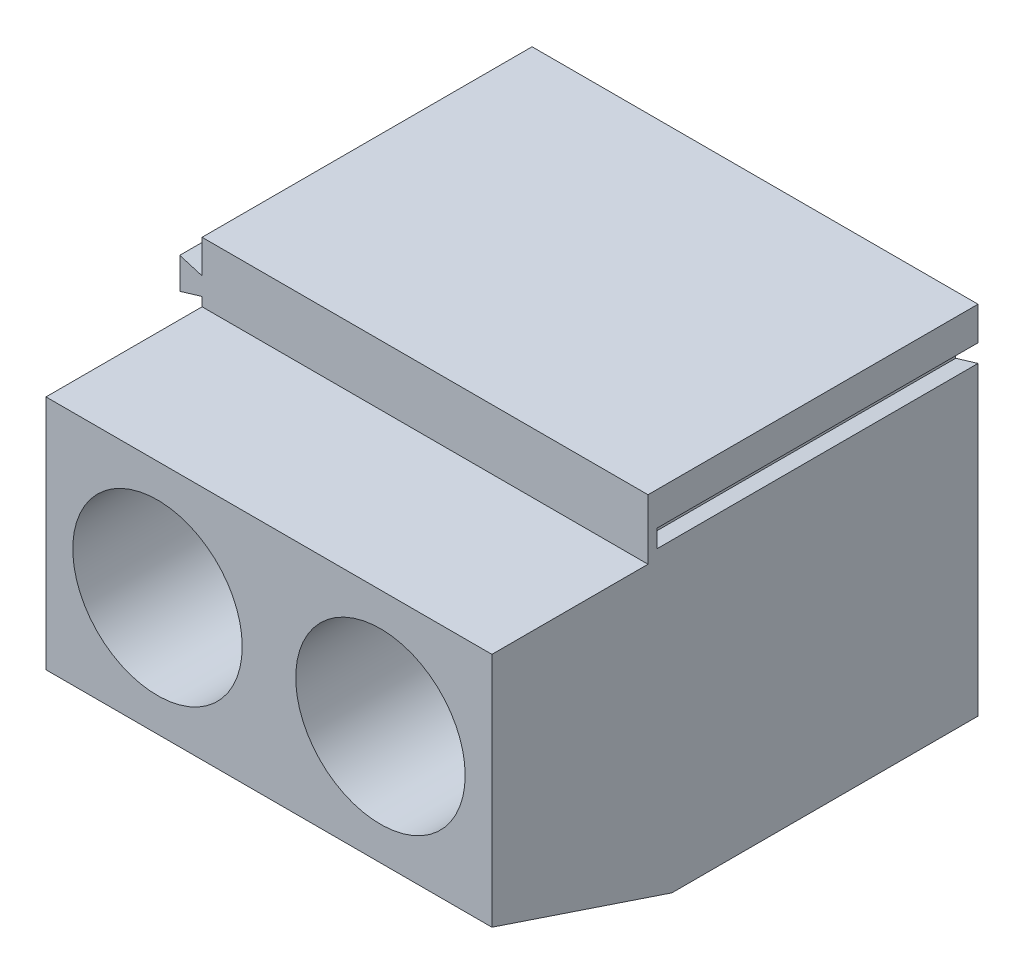
SolidWorks part; units mm, degrees
ref_plane "Front Plane" through (0, 0, 0) normal (0, 0, 1) x (1, 0, 0)
ref_plane "Top Plane" through (0, 0, 0) normal (0, 1, 0) x (1, 0, 0)
ref_plane "Right Plane" through (0, 0, 0) normal (1, 0, 0) x (0, 0, -1)
sketch "Sketch1" plane through (0, 0, 0) normal (0, 0, 1) x (1, 0, 0)
  line L1 (-5, 4) -> (5, 4)
  line L2 (-5, 4) -> (-5, -4)
  line L3 (-5, -4) -> (5, -4)
  line L4 (5, 4) -> (5, -4)
  line L5 (-5, 4) -> (5, -4) construction
  line L6 (-5, -4) -> (5, 4) construction
  point P0 (0, 0)
  dimension "D1" = 10
  dimension "D2" = 8
  dimension "D3" = 4
extrude "Boss-Extrude1" add sketch "Sketch1" along normal blind 10.9
chamfer "Chamfer1" distance 1.35 angle 71.5 1 edges at (0, -4, 10.9)
sketch "Sketch2" plane through (0, 4, 0) normal (0, 1, 0) x (1, 0, 0)
  line L0 (5, -10.9) -> (5, 0) construction
  line L1 (-5, -10.9) -> (5, -10.9)
  line L2 (-5, -10.9) -> (-5, -7.4)
  line L3 (-5, -7.4) -> (5, -7.4)
  line L4 (5, -10.9) -> (5, -7.4)
  dimension "D1" = 3.5
extrude "Cut-Extrude1" cut sketch "Sketch2" against normal blind 1.35
sketch "Sketch3" plane through (0, -4, 0) normal (0, -1, 0) x (1, 0, 0)
  line L0 (0, 0) -> (0, 6.8653) construction
  line L1 (-4.475, 5.65) -> (-0.475, 5.65)
  line L2 (-4.475, 5.65) -> (-4.475, 0.65)
  line L3 (-4.475, 0.65) -> (-0.475, 0.65)
  line L4 (-0.475, 5.65) -> (-0.475, 0.65)
  line L5 (0.475, 5.65) -> (4.475, 5.65)
  line L6 (0.475, 5.65) -> (0.475, 0.65)
  line L7 (0.475, 0.65) -> (4.475, 0.65)
  line L8 (4.475, 5.65) -> (4.475, 0.65)
  line L9 (-5, 0) -> (5, 0) construction
  line L10 (5, 6.8653) -> (-5, 6.8653) construction
  point P8 (4.3875, 1.8004)
  point P15 (0.4239, 5.65)
  dimension "D1" = 4
  dimension "D2" = 0.65
  dimension "D3" = 5
  dimension "D4" = 0.95
extrude "Cut-Extrude2" cut sketch "Sketch3" against normal blind 7
chamfer "Chamfer2" distance 1.2 angle 45 2 edges at (2.475, -4, 5.65) (-2.475, -4, 5.65)
sketch "Sketch4" plane through (0, 0, 0) normal (0, 0, -1) x (-1, 0, 0)
  line L0 (2, 0.7) -> (3, 0.7)
  line L3 (5, -4) -> (-5, -4) construction
  line L4 (3.25, -4) -> (1.75, -4)
  line L5 (1.75, -4) -> (2, -2.4)
  line L6 (2, -2.4) -> (2, 0.7)
  line L7 (-2, 0.7) -> (-2, -2.4)
  line L8 (-2, -2.4) -> (-1.75, -4)
  line L9 (-1.75, -4) -> (-3.25, -4)
  line L10 (-3.25, -4) -> (-3, -2.4)
  line L11 (-3, -2.4) -> (-3, 0.7)
  line L12 (-3, 0.7) -> (-2, 0.7)
  line L13 (0, 0) -> (0, -4) construction
  line L14 (-5, 4) -> (5, 4) construction
  line L15 (3, 0.7) -> (3, -2.4)
  line L16 (3, -2.4) -> (3.25, -4)
  line L17 (2.5, -4) -> (2.5, 0.7) construction
  line L18 (-2.5, -4) -> (-2.5, 0.7) construction
  point P17 (2.5, -4)
  point P18 (2.5, 0.7)
  point P19 (-2.5, -4)
  point P20 (-2.5, 0.7)
  dimension "D1" = 3.1
  dimension "D2" = 3.3
  dimension "D3" = 1.5
  dimension "D4" = 5
  dimension "D5" = 1
extrude "Cut-Extrude3" cut sketch "Sketch4" against normal up to surface (0.65 mm away) up to face at (-2.475, -0.5, 0.65)
sketch "Sketch5" plane through (0, 0, 10.9) normal (0, 0, 1) x (1, 0, 0)
  line L0 (-5, 2.65) -> (-5, -2.65) construction
  line L1 (0, 0) -> (0, -2.65) construction
  line L2 (-5, -2.65) -> (5, -2.65) construction
  circle A0 centre (-2.5, 0) radius 1.9
  circle A1 centre (2.5, 0) radius 1.9
  point P7 (-5, 0)
  dimension "D2" = 3.8
  dimension "D1" = 5
extrude "Cut-Extrude4" cut sketch "Sketch5" along direction (0, 0, 1) on the side against the normal up to surface (5.25 mm away) contours A0 | A1
sketch "Sketch6" plane through (0, 0, 0) normal (0, 0, -1) x (-1, 0, 0)
  line L0 (5, 3.25) -> (5, 2.85)
  line L1 (5, 4) -> (5, -4) construction
  line L2 (5, 2.85) -> (5.5, 2.7)
  line L3 (5.5, 2.7) -> (5.5, 3.4)
  line L4 (5.5, 3.4) -> (5, 3.25)
  line L5 (5, 3.05) -> (5.5, 3.05) construction
  line L6 (-5, 4) -> (5, 4) construction
  dimension "D1" = 0.7
  dimension "D2" = 1.3
  dimension "D3" = 0.4
  dimension "D4" = 0.5
extrude "Boss-Extrude3" add sketch "Sketch6" against normal up to surface (7.4 mm away) up to face at (0, 3.325, 7.4)
sketch "Sketch7" plane through (0, 0, 0) normal (0, 0, -1) x (-1, 0, 0)
  line L0 (-5, 3.25) -> (-4.5, 3.4)
  line L2 (-4.5, 3.4) -> (-4.5, 2.7)
  line L3 (-4.5, 2.7) -> (-5, 2.85)
  line L4 (-5, 2.85) -> (-5, 3.25)
  line L5 (-5, 3.05) -> (-4.5, 3.05) construction
  line L6 (-5, 4) -> (5, 4) construction
  line L7 (-5, -4) -> (-5, 4) construction
  point P10 (-5, 2.85)
  dimension "D1" = 0.7
  dimension "D2" = 0.4
  dimension "D3" = 1.3
  dimension "D4" = 0.5
extrude "Cut-Extrude5" cut sketch "Sketch7" against normal offset from surface (7.2 mm away) 0.2 up to face at (-2.625, 3.1875, 7.4)
